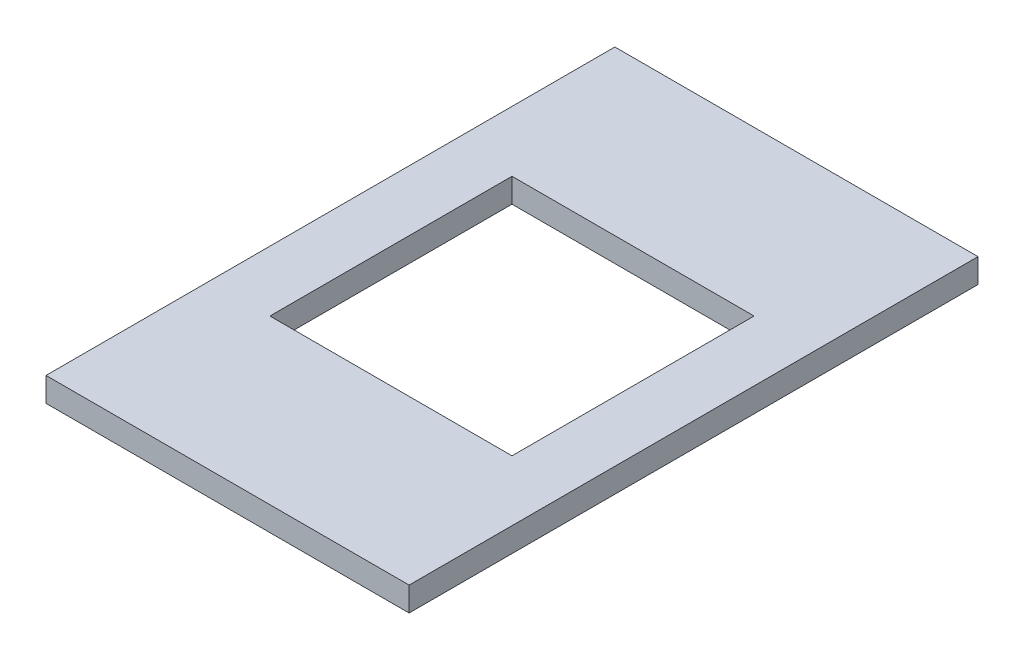
SolidWorks part; units mm, degrees
ref_plane "Front Plane" through (0, 0, 0) normal (0, 0, 1) x (1, 0, 0)
ref_plane "Top Plane" through (0, 0, 0) normal (0, 1, 0) x (1, 0, 0)
ref_plane "Right Plane" through (0, 0, 0) normal (1, 0, 0) x (0, 0, -1)
sketch "Sketch1" plane through (0, 0, 0) normal (0, 1, 0) x (1, 0, 0)
  line L1 (0, 0) -> (-150, 0)
  line L2 (0, 0) -> (0, 30)
  line L3 (0, 30) -> (-150, 30)
  line L4 (-150, 0) -> (-150, 30)
  dimension "D1" = 30
  dimension "D2" = 150
extrude "Boss-Extrude1" add sketch "Sketch1" along normal blind 10
sketch "Sketch8" plane through (0, 0, 0) normal (0, -1, 0) x (-1, 0, 0)
  line L0 (150, 0) -> (0, 30)
  line L1 (150, 30) -> (0, 0)
  line L2 (150, 0) -> (0, 0) construction
sketch "Sketch9" plane through (0, 0, 0) normal (0, -1, 0) x (1, 0, 0)
  line L0 (-150, -30) -> (0, 0) construction
  line L1 (0, -132.5) -> (-150, -132.5)
  line L2 (0, -132.5) -> (0, 102.5)
  line L3 (0, 102.5) -> (-150, 102.5)
  line L4 (-150, -132.5) -> (-150, 102.5)
  line L5 (0, -132.5) -> (-150, 102.5) construction
  line L6 (0, 102.5) -> (-150, -132.5) construction
  line L8 (-125, -65) -> (-25, -65)
  line L9 (-125, -65) -> (-125, 35)
  line L10 (-125, 35) -> (-25, 35)
  line L11 (-25, -65) -> (-25, 35)
  line L12 (-125, -65) -> (-25, 35) construction
  line L13 (-125, 35) -> (-25, -65) construction
  point P0 (-75, -15)
  point P7 (-75, -15)
  point P12 (-75, 102.5)
  point P13 (-75, -132.5)
  dimension "D1" = 235
  dimension "D2" = 150
  dimension "D3" = 100
  dimension "D4" = 100
extrude "Boss-Extrude3" add sketch "Sketch9" along normal blind 10
sketch "Sketch25" plane through (0, 0, 0) normal (0, 1, 0) x (1, 0, 0)
  line L1 (0, 30) -> (-150, 30)
  line L2 (0, 30) -> (0, 0)
  line L3 (0, 0) -> (-150, 0)
  line L4 (-150, 30) -> (-150, 0)
extrude "Cut-Extrude2" cut sketch "Sketch25" along normal blind 10
sketch "Alignment Sketch" plane through (0, 0, 0) normal (0, 1, 0) x (1, 0, 0)
  line L0 (-150, 132.5) -> (0, 132.5) construction
  line L1 (0, 132.5) -> (0, -102.5) construction
  point P0 (-75, 132.5)
  point P1 (0, 15)
sketch "Alignment Sketch 2" plane through (0, 0, -132.5) normal (0, 0, -1) x (-1, 0, 0)
  line L0 (75, 0) -> (75, -10) construction
  line L1 (150, -10) -> (0, -10) construction
